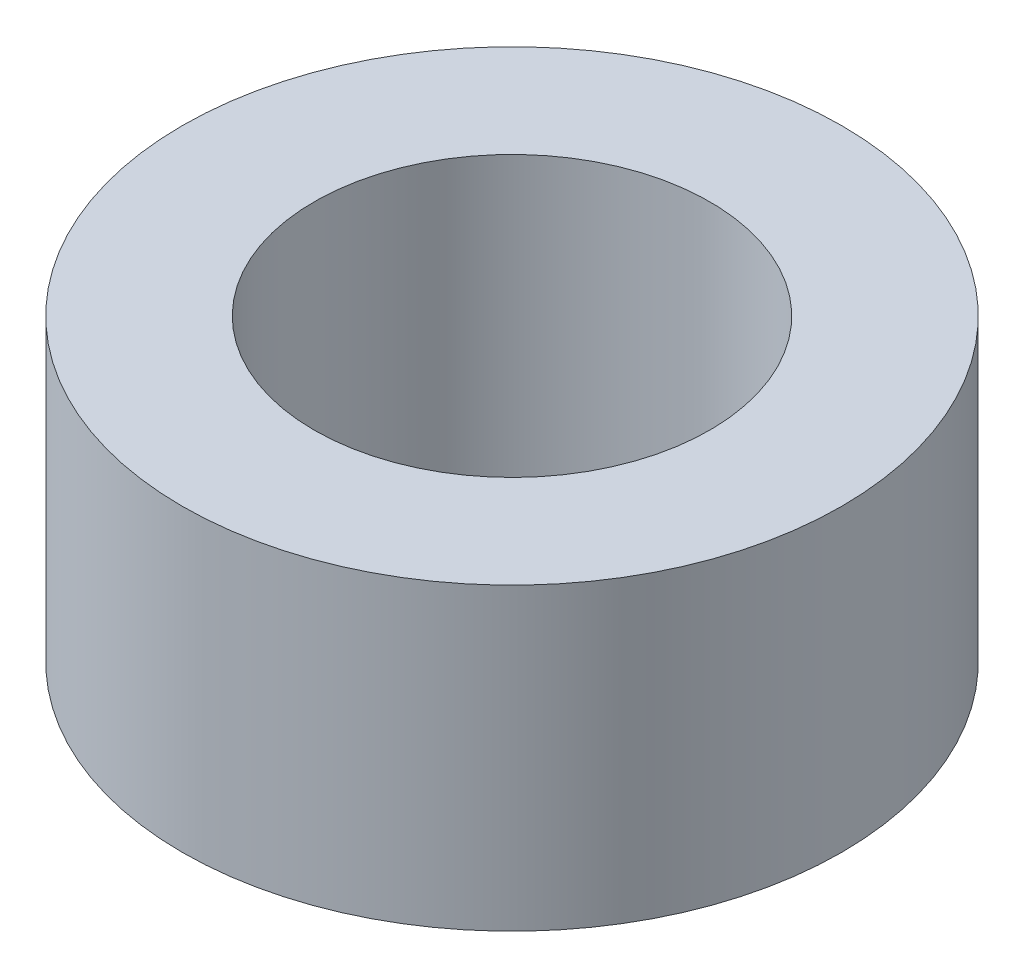
SolidWorks part; units mm, degrees
ref_plane "Front Plane" through (0, 0, 0) normal (0, 0, 1) x (1, 0, 0)
ref_plane "Top Plane" through (0, 0, 0) normal (0, 1, 0) x (1, 0, 0)
ref_plane "Right Plane" through (0, 0, 0) normal (1, 0, 0) x (0, 0, -1)
sketch "Sketch1" plane through (0, 0, 0) normal (0, 1, 0) x (1, 0, 0)
  line L1 (5.5, -5.5) -> (-5.5, -5.5)
  line L2 (5.5, -5.5) -> (5.5, 5.5)
  line L3 (5.5, 5.5) -> (-5.5, 5.5)
  line L4 (-5.5, -5.5) -> (-5.5, 5.5)
  line L5 (5.5, -5.5) -> (-5.5, 5.5) construction
  line L6 (5.5, 5.5) -> (-5.5, -5.5) construction
  point P0 (0, 0)
  dimension "D1" = 11
extrude "Boss-Extrude1" add sketch "Sketch1" along normal blind 5
hole_wizard "M6 Clearance Hole1" positions "Sketch2" profile "Sketch3" hole size "M6" standard "ANSI Metric" end condition up to next
sketch "Sketch2" plane through (0, 5, 0) normal (0, 1, 0) x (1, 0, 0)
  point P0 (0, 0)
sketch "Sketch3" plane through (0, 5, 0) normal (1, 0, 0) x (0, 0, 1)
  line L0 (0, 0) -> (0, 5)
  line L1 (0, 5) -> (3.3, 5)
  line L2 (3.3, 5) -> (3.3, 0)
  line L5 (3.3, 0) -> (0, 0)
  line L11 (0, -6.35) -> (0, 107.95) construction
  dimension "Thru Hole Dia." = 6.6
  dimension "Thru Hole Depth" = 5
sketch "Sketch4" plane through (0, 5, 0) normal (0, 1, 0) x (1, 0, 0)
  line L0 (5.5, 5.5) -> (-5.5, 5.5) construction
  circle A0 centre (0, 0) radius 5.5
extrude "Cut-Extrude1" cut sketch "Sketch4" against normal through all flip side to cut
